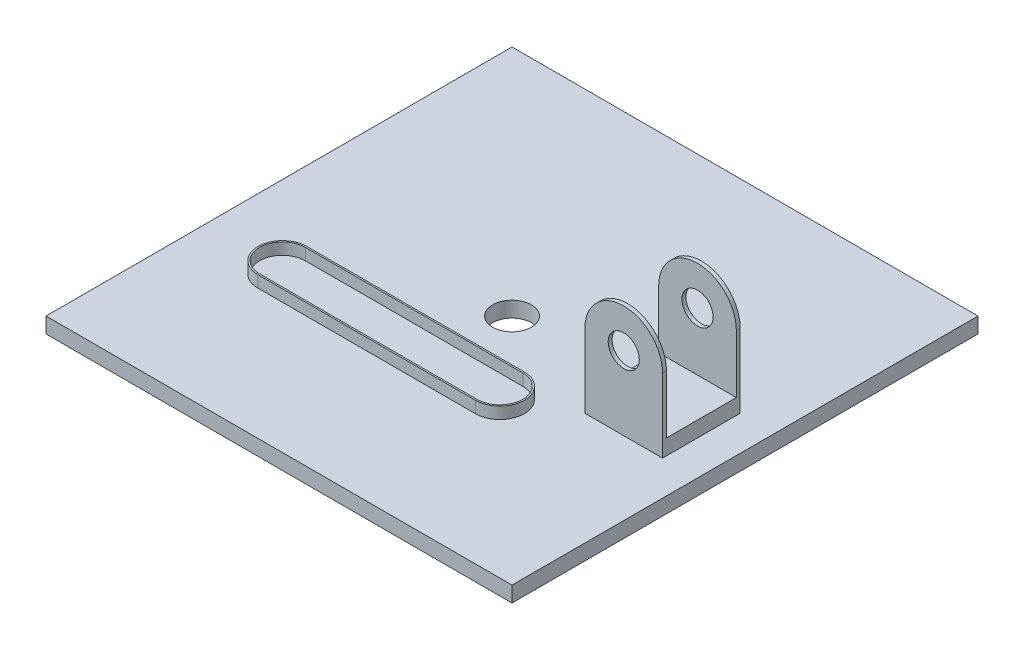
SolidWorks part; units mm, degrees
ref_plane "前视基准面" through (0, 0, 0) normal (0, 0, 1) x (1, 0, 0)
ref_plane "上视基准面" through (0, 0, 0) normal (0, 1, 0) x (1, 0, 0)
ref_plane "右视基准面" through (0, 0, 0) normal (1, 0, 0) x (0, 0, -1)
sketch "草图1" plane through (0, 0, 0) normal (0, 1, 0) x (1, 0, 0)
  line L1 (-300, -300) -> (300, -300)
  line L2 (-300, -300) -> (-300, 300)
  line L3 (-300, 300) -> (300, 300)
  line L4 (300, -300) -> (300, 300)
  line L5 (-300, -300) -> (300, 300) construction
  line L6 (-300, 300) -> (300, -300) construction
  point P0 (0, 0)
  dimension "D1" = 600
  dimension "D2" = 600
extrude "凸台-拉伸1" add sketch "草图1" along normal blind 20
sketch "草图2" plane through (0, 20, 0) normal (0, 1, 0) x (1, 0, 0)
  line L0 (-334.5084, -9.3033) -> (444.4517, -12.4275) construction
  line L2 (155.349, -61.4685) -> (255.349, -61.4685)
  line L3 (155.349, -61.4685) -> (155.349, 38.5315)
  line L4 (155.349, 38.5315) -> (255.349, 38.5315)
  line L5 (255.349, -61.4685) -> (255.349, 38.5315)
  line L6 (155.349, -61.4685) -> (255.349, 38.5315) construction
  line L7 (155.349, 38.5315) -> (255.349, -61.4685) construction
  point P2 (205.349, -11.4685)
  dimension "D1" = 100
extrude "凸台-拉伸2" add sketch "草图2" along normal blind 20
sketch "草图3" plane through (0, 0, 61.4685) normal (0, 0, 1) x (1, 0, 0)
  line L0 (255.349, 114.7665) -> (255.349, 39.3699)
  line L1 (155.349, 114.7665) -> (155.349, 40)
  line L2 (155.349, 40) -> (155.349, 20) construction
  line L3 (155.349, 40) -> (255.349, 40) construction
  arc A0 (155.349, 114.7665) -> (255.349, 114.7665) centre (205.349, 114.7665) cw
  circle A1 centre (205.349, 114.7665) radius 20
  line M3 (255.349, 40) -> (155.349, 40)
  dimension "D1" = 40
extrude "凸台-拉伸3" add sketch "草图3" against normal blind 5 contours A0 L1 L0 A1 M3
sketch "草图5" plane through (0, 0, -38.5315) normal (0, 0, -1) x (-1, 0, 0)
  line L0 (-155.349, 114.7665) -> (-155.349, 40)
  line L1 (-255.349, 114.7665) -> (-255.349, 40)
  arc A0 (-255.349, 114.7665) -> (-155.349, 114.7665) centre (-205.349, 114.7665) cw
  arc A1 (-155.349, 114.7665) -> (-255.349, 114.7665) centre (-205.349, 114.7665) ccw construction
  circle A2 centre (-205.349, 114.7665) radius 20
  line M3 (-155.349, 40) -> (-255.349, 40)
extrude "凸台-拉伸4" add sketch "草图5" against normal blind 5 contours A0 L1 L0 A2 M3
sketch "草图6" plane through (0, 20, 0) normal (0, 1, 0) x (1, 0, 0)
  line L0 (205.349, -61.4685) -> (205.349, -71.4685)
  line L1 (155.349, -61.4685) -> (255.349, -61.4685) construction
  line L2 (205.349, -71.4685) -> (205.349, -100.9685)
  line L3 (85.3548, -100.9685) -> (-194.6452, -100.9685) construction
  line L6 (85.3548, -130.4685) -> (-194.6452, -130.4685)
  line L7 (85.3548, -71.4685) -> (-194.6452, -71.4685)
  arc A2 (85.3548, -130.4685) -> (85.3548, -71.4685) centre (85.3548, -100.9685) ccw
  arc A3 (-194.6452, -71.4685) -> (-194.6452, -130.4685) centre (-194.6452, -100.9685) ccw
  point P7 (-54.6452, -100.9685)
  dimension "D3" = 29.5
  dimension "D1" = 10
  dimension "D2" = 29.5
  dimension "D4" = 280
extrude "拉伸-薄壁1" add sketch "草图6" along normal blind 15 thin
sketch "草图7" plane through (0, 20, 0) normal (0, 1, 0) x (1, 0, 0)
  circle A0 centre (0, 0) radius 25
  dimension "D1" = 50
extrude "切除-拉伸1" cut sketch "草图7" against normal up to surface (20 mm away) up to face at (0, 0, 0)
